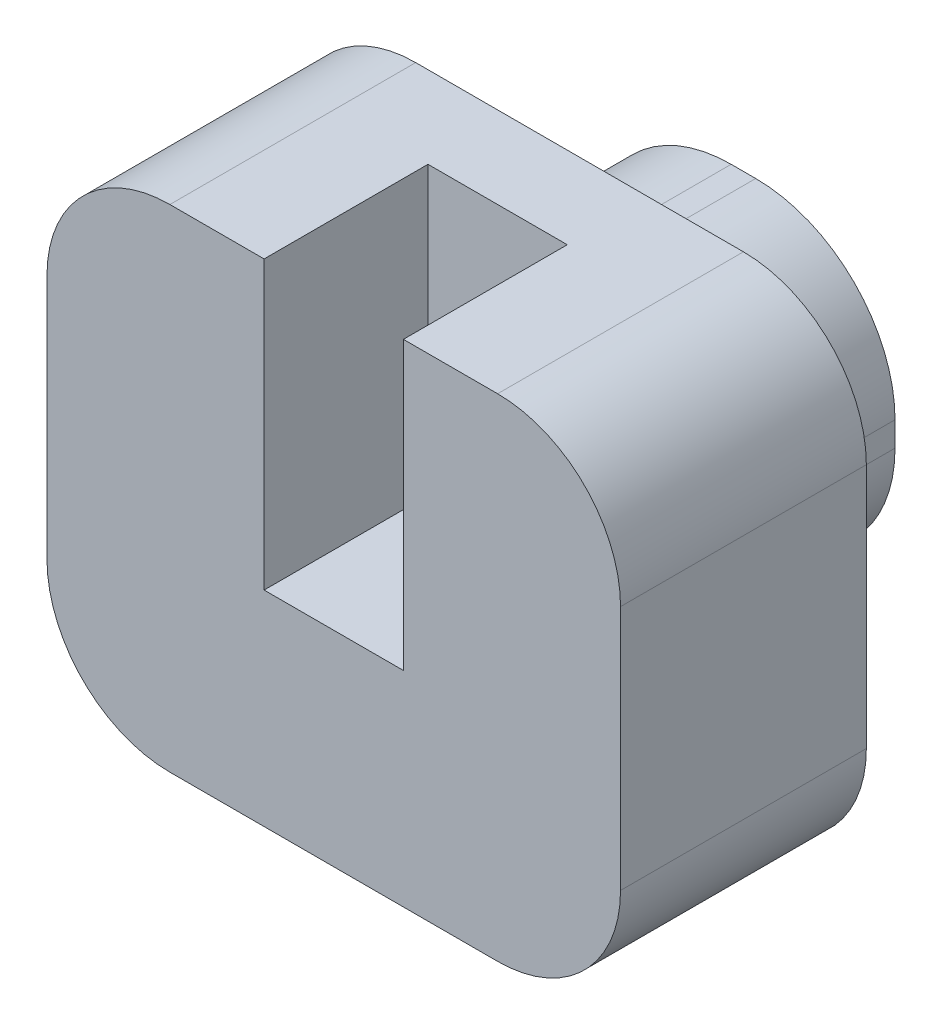
SolidWorks part; units mm, degrees
ref_plane "Спереди" through (0, 0, 0) normal (0, 0, 1) x (1, 0, 0)
ref_plane "Сверху" through (0, 0, 0) normal (0, 1, 0) x (1, 0, 0)
ref_plane "Справа" through (0, 0, 0) normal (1, 0, 0) x (0, 0, -1)
sketch "Эскиз1" plane through (0, 0, 0) normal (0, 0, 1) x (1, 0, 0)
  line L1 (-0.15, -1.85) -> (0.15, -1.85)
  line L2 (-1.85, -0.15) -> (-1.85, 0.15)
  line L3 (-0.15, 1.85) -> (0.15, 1.85)
  line L4 (1.85, -0.15) -> (1.85, 0.15)
  line L5 (-1.85, -1.85) -> (1.85, 1.85) construction
  line L6 (-1.85, 1.85) -> (1.85, -1.85) construction
  arc A0 (-1.85, -0.15) -> (-0.15, -1.85) centre (-0.15, -0.15) ccw
  arc A1 (1.85, 0.15) -> (0.15, 1.85) centre (0.15, 0.15) ccw
  arc A2 (-0.15, 1.85) -> (-1.85, 0.15) centre (-0.15, 0.15) ccw
  arc A3 (1.85, -0.15) -> (0.15, -1.85) centre (0.15, -0.15) cw
  point P0 (0, 0)
  dimension "D3" = 1.7
  dimension "D1" = 3.7
  dimension "D2" = 3.7
extrude "Бобышка-Вытянуть1" add sketch "Эскиз1" along normal blind 2
sketch "Эскиз2" plane through (0, 0, 2) normal (0, 0, 1) x (1, 0, 0)
  line L1 (-2, -3) -> (2, -3)
  line L2 (-3.5, -1.5) -> (-3.5, 1.5)
  line L3 (-2, 3) -> (2, 3)
  line L4 (3.5, -1.5) -> (3.5, 1.5)
  line L5 (-3.5, -3) -> (3.5, 3) construction
  line L6 (-3.5, 3) -> (3.5, -3) construction
  arc A0 (2, -3) -> (3.5, -1.5) centre (2, -1.5) ccw
  arc A1 (-2, -3) -> (-3.5, -1.5) centre (-2, -1.5) cw
  arc A2 (3.5, 1.5) -> (2, 3) centre (2, 1.5) ccw
  arc A3 (-3.5, 1.5) -> (-2, 3) centre (-2, 1.5) cw
  point P0 (0, 0)
  dimension "D3" = 1.5
  dimension "D1" = 7
  dimension "D2" = 6
extrude "Бобышка-Вытянуть2" add sketch "Эскиз2" along normal blind 3 contours A3 L2 A1 L1 A0 L4 A2 L3
sketch "Эскиз4" plane through (0, 3, 0) normal (0, 1, 0) x (1, 0, 0)
  line L0 (3.5, -5) -> (3.5, -2) construction
  line L1 (-2, -5) -> (2, -5) construction
  line L2 (-0.85, -5) -> (0.85, -5)
  line L3 (-0.85, -5) -> (-0.85, -3)
  line L4 (-0.85, -3) -> (0.85, -3)
  line L5 (0.85, -5) -> (0.85, -3)
  line L6 (-0.85, -5) -> (0.85, -3) construction
  line L7 (-0.85, -3) -> (0.85, -5) construction
  point P3 (0, -4)
  point P8 (0, -5)
  dimension "D1" = 2
  dimension "D2" = 1.7
  dimension "D3" = 3.5
extrude "Вырез-Вытянуть1" cut sketch "Эскиз4" against normal blind 3.5
equation "\"D3@Эскиз4\"=\"D1@Эскиз2\"/2"
